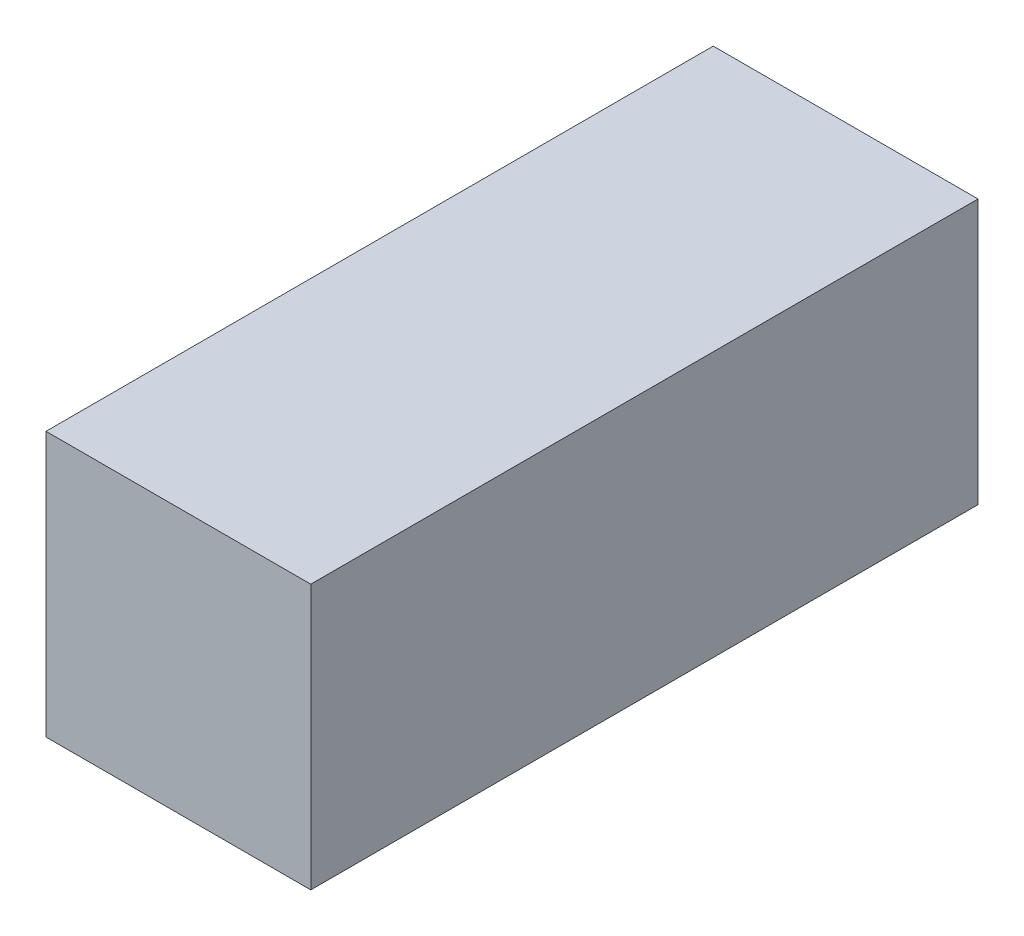
SolidWorks part; units mm, degrees
ref_plane "Front Plane" through (0, 0, 0) normal (0, 0, 1) x (1, 0, 0)
ref_plane "Top Plane" through (0, 0, 0) normal (0, 1, 0) x (1, 0, 0)
ref_plane "Right Plane" through (0, 0, 0) normal (1, 0, 0) x (0, 0, -1)
sketch "Sketch1" plane through (0, 0, 0) normal (0, 0, 1) x (1, 0, 0)
  line L1 (0, 0) -> (1270, 0)
  line L2 (0, 0) -> (0, 1270)
  line L3 (0, 1270) -> (1270, 1270)
  line L4 (1270, 0) -> (1270, 1270)
  dimension "D1" = 1270
  dimension "D2" = 1270
extrude "Boss-Extrude1" add sketch "Sketch1" along normal blind 3200.4
